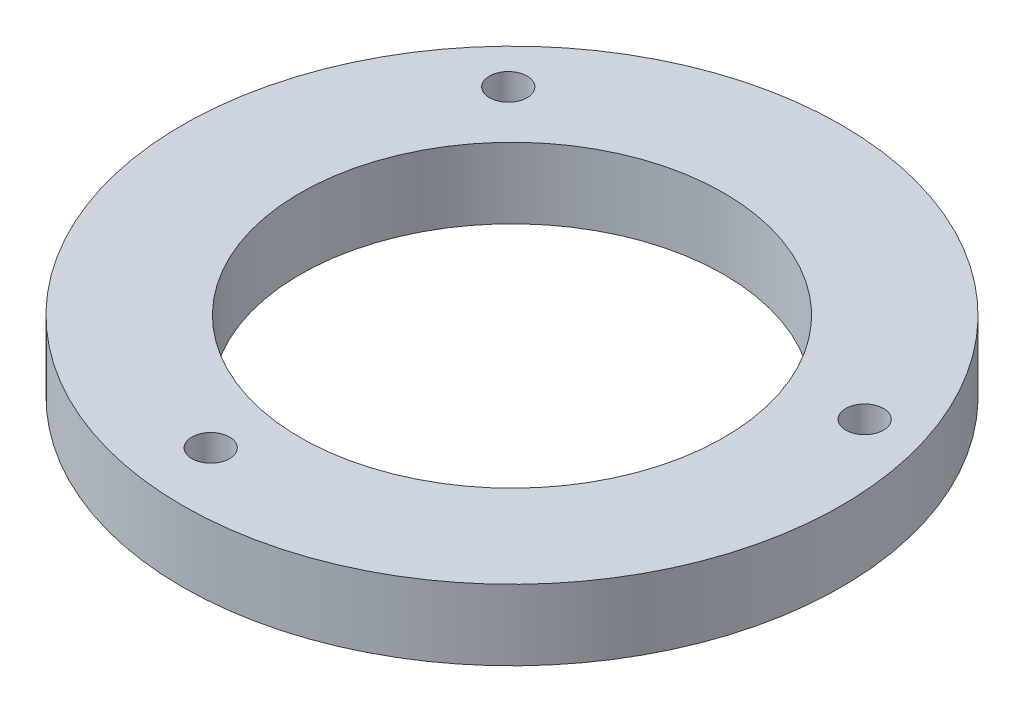
SolidWorks part; units mm, degrees
ref_plane "Front Plane" through (0, 0, 0) normal (0, 0, 1) x (1, 0, 0)
ref_plane "Top Plane" through (0, 0, 0) normal (0, 1, 0) x (1, 0, 0)
ref_plane "Right Plane" through (0, 0, 0) normal (1, 0, 0) x (0, 0, -1)
sketch "Sketch1" plane through (0, 0, 0) normal (0, 1, 0) x (1, 0, 0)
  circle A0 centre (0, 0) radius 35.56
  circle A1 centre (0, 0) radius 22.86
  dimension "D1" = 71.12
  dimension "D2" = 45.72
extrude "Boss-Extrude1" add sketch "Sketch1" along normal blind 7.62
sketch "Sketch2" plane through (0, 7.62, 0) normal (0, 1, 0) x (1, 0, 0)
  line L0 (-3.8637, -28.648) -> (28.7518, 9.2997) construction
  line L1 (28.7518, 9.2997) -> (-21.5402, 21.136) construction
  line L2 (-21.5402, 21.136) -> (-3.8637, -28.648) construction
  circle A0 centre (28.7518, 9.2997) radius 2.032
  circle A1 centre (-3.8637, -28.648) radius 2.032
  circle A2 centre (-21.5402, 21.136) radius 2.032
  point P6 (-24.5459, 16.7209)
  point P7 (-3.6884, -30.338)
  dimension "D1" = 4.064
  dimension "D2" = 49.784
  dimension "D3" = 50.038
  dimension "D4" = 50.292
extrude "Cut-Extrude1" cut sketch "Sketch2" against normal through all
equation "\"Foamcore\" = .1in"
equation "\"MDF\" = .3in"
equation "\"Gmaterial\"= \"MDF\""
equation "\"PVC-ID\" = \"1.590in\""
equation "\"PVC-OD\" = \"1.900in\""
equation "\"PVC-Sleeve-Width\" = \".51in\""
equation "\"D1@Boss-Extrude1\"=\"Gmaterial\""
